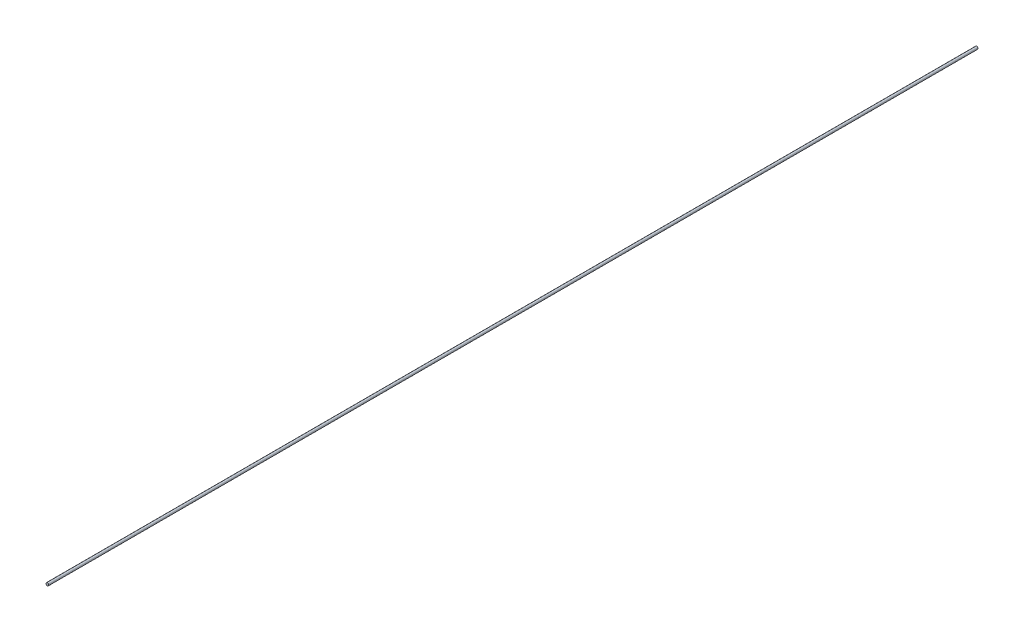
SolidWorks part; units mm, degrees
ref_plane "Plan de face" through (0, 0, 0) normal (0, 0, 1) x (1, 0, 0)
ref_plane "Plan de dessus" through (0, 0, 0) normal (0, 1, 0) x (1, 0, 0)
ref_plane "Plan de droite" through (0, 0, 0) normal (1, 0, 0) x (0, 0, -1)
sketch "Esquisse1" plane through (0, 0, 0) normal (0, 0, 1) x (1, 0, 0)
  circle A0 centre (0, 0) radius 1
  dimension "D1" = 2
extrude "Boss.-Extru.1" add sketch "Esquisse1" along normal blind 700
